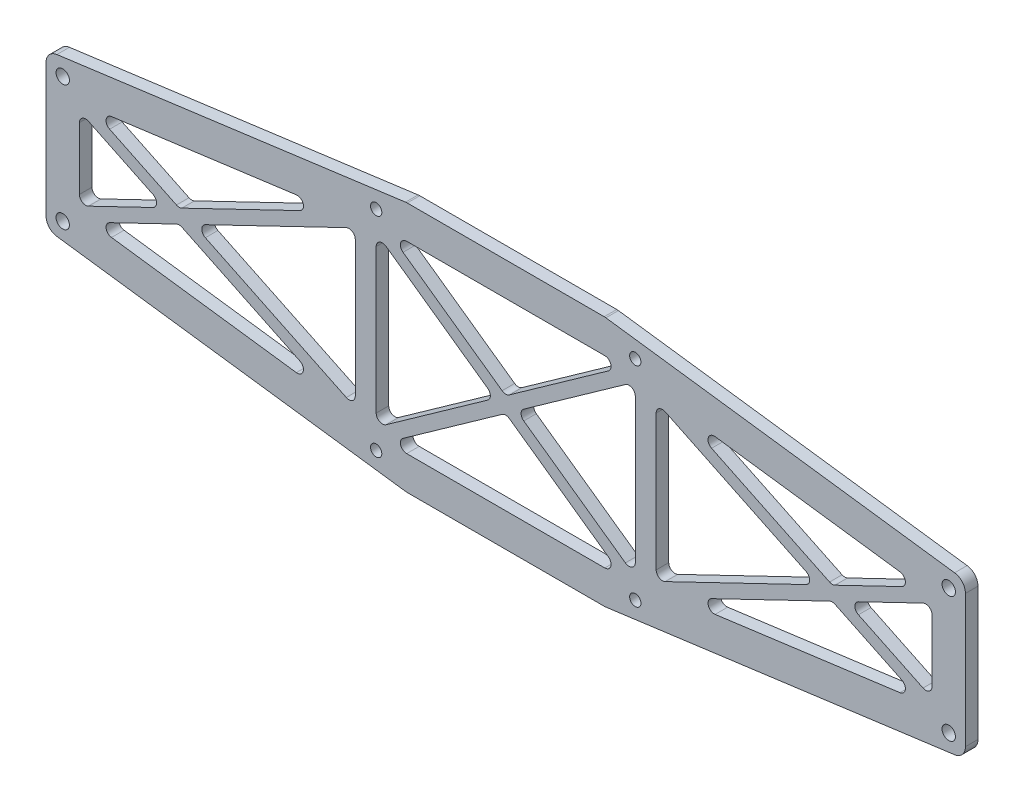
SolidWorks part; units mm, degrees
material "Thornel Mat VMA"
ref_plane "前视基准面" through (0, 0, 0) normal (0, 0, 1) x (1, 0, 0)
ref_plane "上视基准面" through (0, 0, 0) normal (0, 1, 0) x (1, 0, 0)
ref_plane "右视基准面" through (0, 0, 0) normal (1, 0, 0) x (0, 0, -1)
other "Configuration Table"
sketch "草图1" plane through (0, 0, 0) normal (0, 0, 1) x (1, 0, 0)
  line L0 (-116, 0) -> (116, 0) construction
  line L1 (-31, -25) -> (31, -25) construction
  line L2 (-31, -25) -> (-31, 25) construction
  line L3 (-31, 25) -> (31, 25) construction
  line L4 (31, -25) -> (31, 25) construction
  line L5 (-31, -25) -> (31, 25) construction
  line L6 (-31, 25) -> (31, -25) construction
  line L7 (-116, 0) -> (-116, -50000) construction
  line L8 (116, 0) -> (116, -50000) construction
  line L9 (-110, 18.5021) -> (-110, -18.5021)
  line L10 (-106, 15) -> (-106, -15) construction
  line L11 (0, 0) -> (0, -50000) construction
  line L12 (-110, -18.5021) -> (-23.7655, -30)
  line L13 (-23.7655, -30) -> (23.7655, -30)
  line L14 (-23.7655, 30) -> (23.7655, 30)
  line L15 (-110, 18.5021) -> (-23.7655, 30)
  line L16 (110, -18.5021) -> (23.7655, -30)
  line L17 (110, 18.5021) -> (110, -18.5021)
  line L18 (110, 18.5021) -> (23.7655, 30)
  circle A0 centre (-31, 25) radius 1.35
  circle A1 centre (31, 25) radius 1.35
  circle A2 centre (-31, -25) radius 1.35
  circle A3 centre (31, -25) radius 1.35
  circle A4 centre (-106, 15) radius 1.6
  circle A5 centre (-106, -15) radius 1.6
  circle A6 centre (-106, -15) radius 4 construction
  circle A7 centre (-31, -25) radius 4 construction
  circle A8 centre (106, -15) radius 1.6
  circle A9 centre (106, 15) radius 1.6
  point P0 (0, 0)
  point P13 (0, 0)
  point P22 (-106, 0)
  point P33 (-110, 0)
  point P34 (0, -30)
  point P37 (0, 30)
  dimension "D3" = 2.7
  dimension "D6" = 3.2
  dimension "D10" = 8
  dimension "D1" = 62
  dimension "D2" = 50
  dimension "D4" = 232
  dimension "D7" = 30
  dimension "D5" = 10
  dimension "D8" = 4
  dimension "D9" = 5
extrude "凸台-拉伸1" add sketch "草图1" along normal mid plane 3
fillet "圆角1" radius 3 8 edges at (23.7655, -30, 0) (-23.7655, -30, 0) (-110, -18.5021, 0) (-23.7655, 30, 0) (23.7655, 30, 0) (110, 18.5021, 0) (110, -18.5021, 0) (-110, 18.5021, 0)
sketch "草图2" plane through (0, 0, 1.5) normal (0, 0, 1) x (1, 0, 0)
  line L0 (23.5664, 30) -> (-23.5664, 30) construction
  line L1 (-31, -22) -> (31, -22)
  line L2 (-31, -22) -> (-31, 22)
  line L3 (-31, 22) -> (31, 22)
  line L4 (31, -22) -> (31, 22)
  line L5 (-31, -22) -> (31, 22) construction
  line L6 (-31, 22) -> (31, -22) construction
  line L7 (0, 0) -> (50000, 0) construction
  line L8 (0, 0) -> (0, -50000) construction
  line L9 (-36, -20.2979) -> (-36, 20.2979)
  line L10 (-36, 20.2979) -> (-102, 11.4979)
  line L11 (-102, 11.4979) -> (-102, -11.4979)
  line L12 (-23.9629, 29.9737) -> (-107.3965, 18.8492) construction
  line L13 (-110, 15.8755) -> (-110, -15.8755) construction
  line L14 (-36, -20.2979) -> (-102, -11.4979)
  line L15 (-102, 11.4979) -> (-36, -20.2979) construction
  line L16 (-102, -11.4979) -> (-36, 20.2979) construction
  line L17 (-99.2931, -11.8589) -> (-36, 18.6329)
  line L18 (-102, 9.8329) -> (-40.7787, -19.6608)
  line L19 (-102, -9.8329) -> (-40.7787, 19.6608)
  line L20 (-99.2931, 11.8589) -> (-36, -18.6329)
  line L21 (-101.349, -12.8493) -> (-35.349, 18.9466) construction
  line L22 (-102.651, -10.1466) -> (-36.651, 21.6493) construction
  line L23 (-101.349, 12.8493) -> (-35.349, -18.9466) construction
  line L24 (-102.651, 10.1466) -> (-36.651, -21.6493) construction
  line L25 (102, -11.4979) -> (36, 20.2979) construction
  line L26 (102, 11.4979) -> (36, -20.2979) construction
  line L27 (0, 0) -> (-50000, 0) construction
  line L28 (99.2931, 11.8589) -> (36, -18.6329)
  line L29 (102, -9.8329) -> (40.7787, 19.6608)
  line L30 (102, 9.8329) -> (40.7787, -19.6608)
  line L31 (99.2931, -11.8589) -> (36, 18.6329)
  line L32 (36, -20.2979) -> (102, -11.4979)
  line L33 (102, 11.4979) -> (102, -11.4979)
  line L34 (36, 20.2979) -> (102, 11.4979)
  line L35 (36, -20.2979) -> (36, 20.2979)
  line L36 (-31, 20.1607) -> (28.4082, -22)
  line L37 (-28.4082, -22) -> (31, 20.1607)
  line L38 (-28.4082, 22) -> (31, -20.1607)
  line L39 (-31, -20.1607) -> (28.4082, 22)
  line L40 (-30.1319, 23.2233) -> (31.8681, -20.7767) construction
  line L41 (-31.8681, 20.7767) -> (30.1319, -23.2233) construction
  line L42 (-31.8681, -20.7767) -> (30.1319, 23.2233) construction
  line L43 (-30.1319, -23.2233) -> (31.8681, 20.7767) construction
  point P0 (0, 0)
  point P23 (-36, 0)
  point P24 (-102, 0)
  point P53 (102, 0)
  point P54 (36, 0)
  dimension "D2" = 8
  dimension "D1" = 8
  dimension "D3" = 5
  dimension "D4" = 62
  dimension "D5" = 8
  dimension "D6" = 1.5
  dimension "D7" = 1.5
  dimension "D8" = 1.5
  dimension "D9" = 1.5
extrude "切除-拉伸1" cut sketch "草图2" against normal mid plane 13 contours L10 L20 L19 | L17 L20 L9 | L18 L17 L14 | L11 L19 L18 | L2 L39 L36 | L38 L39 L3 | L37 L38 L4 | L37 L1 L36 | L35 L28 L31 | L34 L29 L28 | L33 L30 L29 | L30 L32 L31
fillet "圆角2" radius 1.5 36 edges at (31, 20.1607, 0) (31, -20.1607, 0) (2.5918, 0, 0) (28.4082, 22, 0) (0, 1.8393, 0) (-28.4082, 22, 0) (36, 18.6329, 0) (74.6772, 0, 0) (36, -18.6329, 0) (-36, 18.6329, 0) (-36, -18.6329, 0) (-74.6772, 0, 0) (-81.5894, 0, 0) (-102, -9.8329, 0) (-102, 9.8329, 0) (99.2931, 11.8589, 0) (78.1333, 1.665, 0) (40.7787, 19.6608, 0) (-78.1333, 1.665, 0) (-99.2931, 11.8589, 0) (-40.7787, 19.6608, 0) (102, -9.8329, 0) (102, 9.8329, 0) (99.2931, -11.8589, 0) (40.7787, -19.6608, 0) (78.1333, -1.665, 0) (-31, 20.1607, 0) (-2.5918, 0, 0) (-31, -20.1607, 0) (-40.7787, -19.6608, 0) (-99.2931, -11.8589, 0) (-78.1333, -1.665, 0) (0, -1.8393, 0) (28.4082, -22, 0) (-28.4082, -22, 0) (81.5894, 0, 0)
